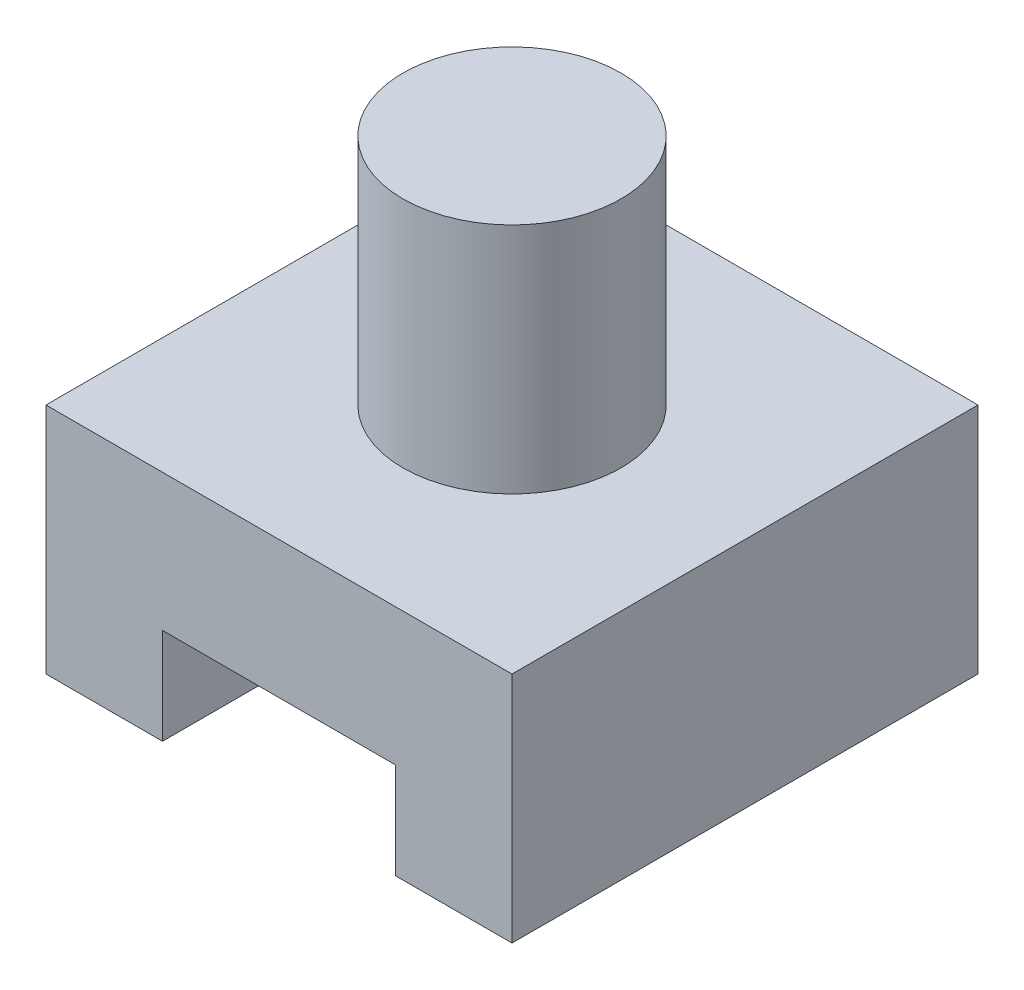
SolidWorks part; units mm, degrees
ref_plane "Front Plane" through (0, 0, 0) normal (0, 0, 1) x (1, 0, 0)
ref_plane "Top Plane" through (0, 0, 0) normal (0, 1, 0) x (1, 0, 0)
ref_plane "Right Plane" through (0, 0, 0) normal (1, 0, 0) x (0, 0, -1)
sketch "Sketch2" plane through (0, 0, 0) normal (0, 1, 0) x (1, 0, 0)
  line L1 (0, 0) -> (40, 0)
  line L2 (0, 0) -> (0, 40)
  line L3 (0, 40) -> (40, 40)
  line L4 (40, 0) -> (40, 40)
  dimension "D1" = 40
  dimension "D2" = 40
extrude "Boss-Extrude1" add sketch "Sketch2" along normal blind 20
sketch "Sketch4" plane through (0, 0, 0) normal (0, 0, 1) x (1, 0, 0)
  line L0 (10, 0) -> (10, 8.2426)
  line L1 (0, 0) -> (40, 0) construction
  line L2 (10, 8.2426) -> (30, 8.2426)
  line L3 (30, 8.2426) -> (30, 0)
  line L4 (40, 20) -> (40, 0) construction
  line L5 (0, 20) -> (0, 0) construction
  line L6 (10, 0) -> (30, 0)
  point P5 (30, 4.1213)
  dimension "D1" = 20
  dimension "D2" = 10
  dimension "D3" = 10
extrude "Cut-Extrude1" cut sketch "Sketch4" against normal blind 44
sketch "Sketch6" plane through (0, 20, 0) normal (0, 1, 0) x (1, 0, 0)
  line L0 (0, 40) -> (0, 0) construction
  line L1 (40, 40) -> (0, 40) construction
  circle A0 centre (20, 20) radius 9.3597
  dimension "D1" = 20
  dimension "D2" = 20
extrude "Boss-Extrude3" add sketch "Sketch6" along normal blind 20
